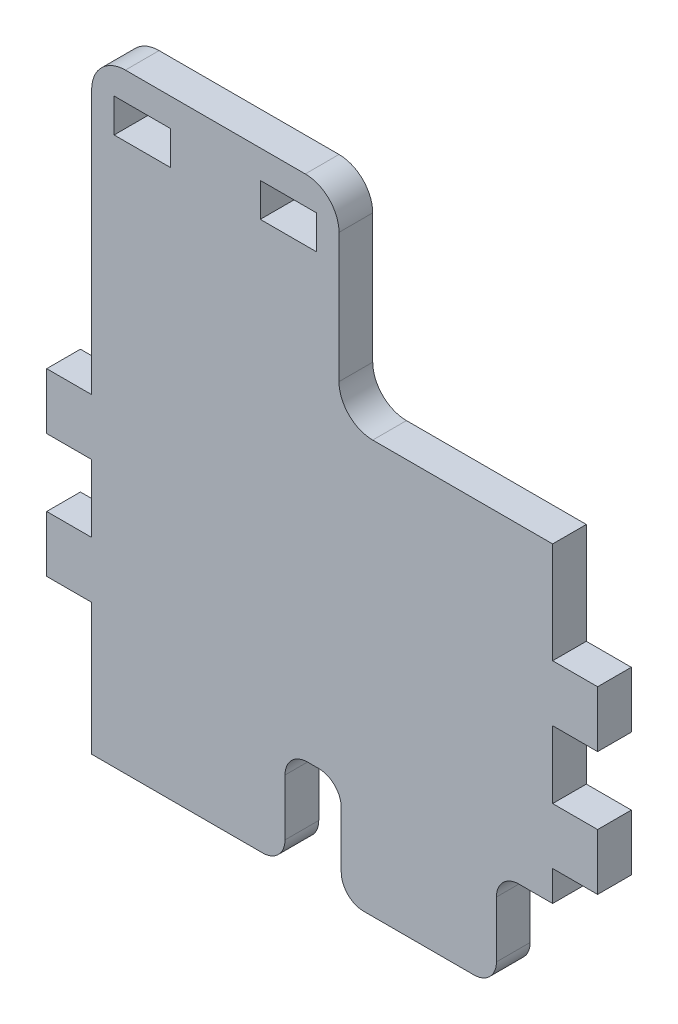
SolidWorks part; units mm, degrees
ref_plane "Front Plane" through (0, 0, 0) normal (0, 0, 1) x (1, 0, 0)
ref_plane "Top Plane" through (0, 0, 0) normal (0, 1, 0) x (1, 0, 0)
ref_plane "Right Plane" through (0, 0, 0) normal (1, 0, 0) x (0, 0, -1)
sketch "草图1" plane through (0, 0, 0) normal (0, 0, 1) x (1, 0, 0)
  line L1 (-20.5, -15) -> (20.5, -15)
  line L2 (-20.5, -15) -> (-20.5, 15)
  line L3 (-20.5, 15) -> (20.5, 15)
  line L4 (20.5, -15) -> (20.5, 15)
  line L5 (-20.5, -15) -> (20.5, 15) construction
  line L6 (-20.5, 15) -> (20.5, -15) construction
  point P0 (0, 0)
  dimension "41" = 41
  dimension "D2" = 30
extrude "凸台-拉伸1" add sketch "草图1" along normal blind 3
sketch "草图2" plane through (0, 0, 3) normal (0, 0, 1) x (1, 0, 0)
  line L0 (0, 15) -> (0, -17.8549) construction
  line L1 (20.5, 15) -> (-20.5, 15) construction
  line L2 (20.5, -15) -> (20.5, 15) construction
  line L3 (20.5, -10) -> (24.5, -10)
  line L4 (20.5, -10) -> (20.5, -5)
  line L5 (20.5, -5) -> (24.5, -5)
  line L6 (24.5, -10) -> (24.5, -5)
  line L7 (20.5, -10) -> (24.5, -5) construction
  line L8 (20.5, -5) -> (24.5, -10) construction
  line L9 (-20.5, -15) -> (20.5, -15) construction
  line L10 (20.5, 6) -> (24.5, 6)
  line L11 (20.5, 6) -> (20.5, 1)
  line L12 (20.5, 1) -> (24.5, 1)
  line L13 (24.5, 6) -> (24.5, 1)
  line L14 (20.5, 6) -> (24.5, 1) construction
  line L15 (20.5, 1) -> (24.5, 6) construction
  line L16 (-20.5, -5) -> (-24.5, -5)
  line L17 (-24.5, -10) -> (-24.5, -5)
  line L18 (-20.5, -10) -> (-24.5, -10)
  line L19 (-20.5, -10) -> (-20.5, -5)
  line L20 (-20.5, 1) -> (-24.5, 1)
  line L21 (-24.5, 6) -> (-24.5, 1)
  line L22 (-20.5, 6) -> (-24.5, 6)
  line L23 (-20.5, 6) -> (-20.5, 1)
  point P9 (22.5, -7.5)
  point P16 (22.5, 3.5)
  dimension "D1" = 4
  dimension "D2" = 5
  dimension "D3" = 4
  dimension "D4" = 5
  dimension "D5" = 6
  dimension "D6" = 5
extrude "凸台-拉伸2" add sketch "草图2" against normal up to surface (3 mm away) up to face at (0, 0, 0)
sketch "草图3" plane through (0, 0, 0) normal (0, 0, -1) x (-1, 0, 0)
  line L1 (20.5, 15) -> (-1.5, 15)
  line L2 (20.5, 15) -> (20.5, 32.5)
  line L3 (20.5, 32.5) -> (-1.5, 32.5)
  line L4 (-1.5, 15) -> (-1.5, 32.5)
  line L5 (20.5, 15) -> (-1.5, 32.5) construction
  line L6 (20.5, 32.5) -> (-1.5, 15) construction
  point P4 (9.5, 23.75)
  dimension "D1" = 22
  dimension "D2" = 17.5
extrude "凸台-拉伸3" add sketch "草图3" against normal up to surface (3 mm away) up to face at (0, -1.6, 3)
sketch "草图4" plane through (0, 0, 0) normal (0, 0, -1) x (-1, 0, 0)
  line L0 (-4.6443, 30) -> (24.6236, 30) construction
  line L1 (20.5, 32.5) -> (-1.5, 32.5) construction
  line L2 (-1.5, 32.5) -> (-1.5, 15) construction
  line L3 (0.5, 30) -> (5.5, 30)
  line L4 (0.5, 30) -> (0.5, 27)
  line L5 (0.5, 27) -> (5.5, 27)
  line L6 (5.5, 30) -> (5.5, 27)
  line L7 (0.5, 30) -> (5.5, 27) construction
  line L8 (0.5, 27) -> (5.5, 30) construction
  line L9 (20.5, 32.5) -> (20.5, 6) construction
  line L10 (13.5, 30) -> (18.5, 30)
  line L11 (13.5, 30) -> (13.5, 27)
  line L12 (13.5, 27) -> (18.5, 27)
  line L13 (18.5, 30) -> (18.5, 27)
  line L14 (13.5, 30) -> (18.5, 27) construction
  line L15 (13.5, 27) -> (18.5, 30) construction
  point P8 (3, 28.5)
  point P15 (16, 28.5)
  dimension "D1" = 2.5
  dimension "D2" = 3
  dimension "D3" = 2
  dimension "D4" = 5
  dimension "D5" = 5
  dimension "D6" = 2
  dimension "D7" = 3
extrude "切除-拉伸1" cut sketch "草图4" against normal blind 10
sketch "草图5" plane through (0, 0, 0) normal (0, 0, -1) x (-1, 0, 0)
  line L0 (20.5, -10) -> (20.5, -15) construction
  line L1 (-20.5, -15) -> (20.5, -15)
  line L2 (-20.5, -15) -> (-20.5, -21.7)
  line L3 (-20.5, -21.7) -> (20.5, -21.7)
  line L4 (20.5, -15) -> (20.5, -21.7)
  line L5 (-20.5, -15) -> (20.5, -21.7) construction
  line L6 (-20.5, -21.7) -> (20.5, -15) construction
  point P4 (0, -18.35)
  dimension "D1" = 6.7
extrude "凸台-拉伸4" add sketch "草图5" against normal up to surface (3 mm away) up to face at (-3, 28.5, 3)
sketch "草图6" plane through (0, 0, 0) normal (0, 0, -1) x (-1, 0, 0)
  line L0 (-20.5, -21.7) -> (-20.5, -10) construction
  line L1 (-20.5, -21.7) -> (20.5, -21.7) construction
  line L2 (-15.5, 4.9036) -> (-15.5, -25.4209) construction
  line L4 (-20.5, 4.9036) -> (-20.5, -23.8286) construction
  line L5 (3.3, -12.7) -> (-1.7, -12.7)
  line L6 (-20.5, -21.7) -> (-15.5, -21.7)
  line L7 (-20.5, -21.7) -> (-20.5, -12.7)
  line L8 (-20.5, -12.7) -> (-15.5, -12.7)
  line L9 (-15.5, -21.7) -> (-15.5, -12.7)
  line L10 (-20.5, -21.7) -> (-15.5, -12.7) construction
  line L11 (-20.5, -12.7) -> (-15.5, -21.7) construction
  line L12 (-1.7, -21.7) -> (-1.7, -12.7)
  line L13 (3.3, -21.7) -> (-1.7, -21.7)
  line L14 (3.3, -21.7) -> (3.3, -12.7)
  point P15 (-18, -17.2)
  dimension "D1" = 13.8
  dimension "D2" = 5
  dimension "D3" = 9
  dimension "D4" = 9
  dimension "D5" = 5
extrude "切除-拉伸2" cut sketch "草图6" against normal blind 10
fillet "圆角1" radius 3 3 edges at (-20.5, 32.5, 1.5) (1.5, 15, 1.5) (1.5, 32.5, 1.5)
fillet "圆角2" radius 2 6 edges at (-3.3, -21.7, 1.5) (-3.3, -12.7, 1.5) (1.7, -12.7, 1.5) (1.7, -21.7, 1.5) (15.5, -21.7, 1.5) (15.5, -12.7, 1.5)
